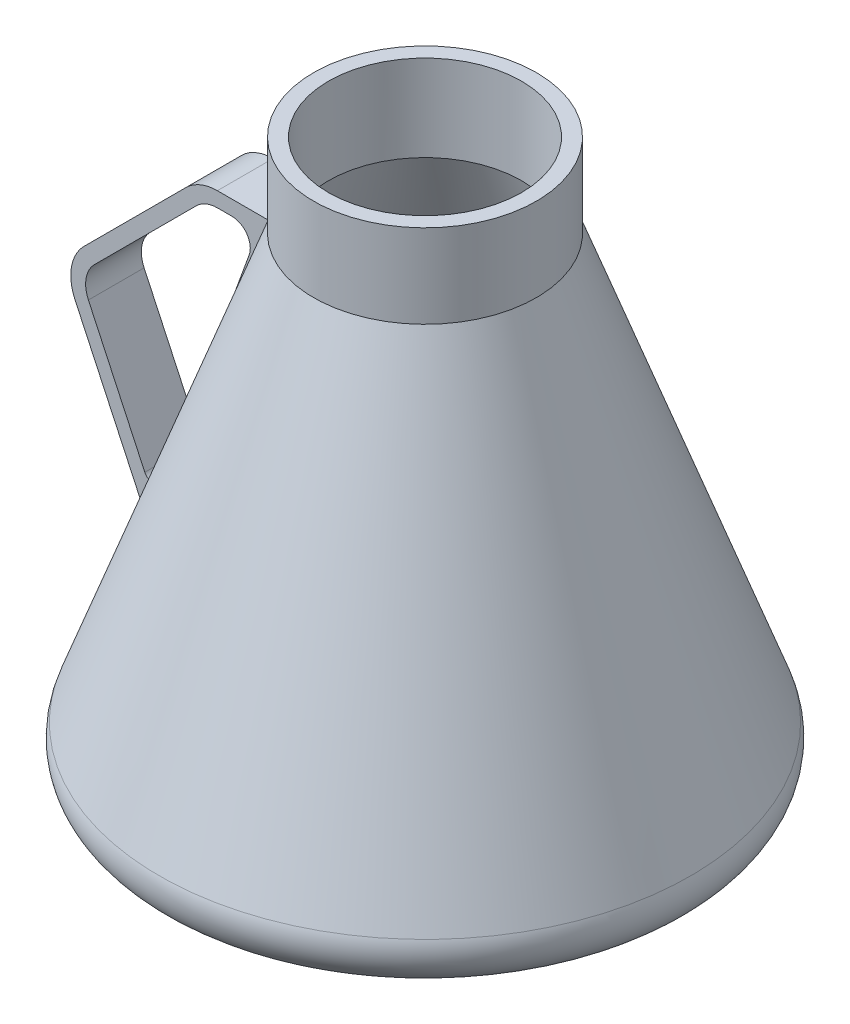
SolidWorks part; units mm, degrees
ref_plane "前视基准面" through (0, 0, 0) normal (0, 0, 1) x (1, 0, 0)
ref_plane "上视基准面" through (0, 0, 0) normal (0, 1, 0) x (1, 0, 0)
ref_plane "右视基准面" through (0, 0, 0) normal (1, 0, 0) x (0, 0, -1)
other "Configuration Table"
sketch "草图1" plane through (0, 0, 0) normal (0, 0, 1) x (1, 0, 0)
  line L0 (0, 0) -> (-124.2494, 0)
  line L1 (-143.0433, 26.8404) -> (-60, 255)
  line L2 (-60, 255) -> (-60, 300)
  line L3 (-60, 300) -> (0, 300)
  line L4 (0, -74.7711) -> (0, 327.4669) construction
  line L5 (0, 0) -> (0, 300)
  line L6 (-8, 8) -> (-124.2494, 8)
  line L7 (-135.5258, 24.1042) -> (-52, 253.5894)
  line L8 (-52, 253.5894) -> (-52, 292)
  line L9 (-52, 292) -> (-8, 292)
  line L10 (-8, 8) -> (-8, 292)
  arc A0 (-143.0433, 26.8404) -> (-124.2494, 0) centre (-124.2494, 20) ccw
  arc A1 (-135.5258, 24.1042) -> (-124.2494, 8) centre (-124.2494, 20) ccw
  dimension "D5" = 20
  dimension "D1" = 300
  dimension "D2" = 20
  dimension "D3" = 60
  dimension "D4" = 45
  dimension "D6" = 8
revolve "旋转2" add sketch "草图1" angle 360 about L4
sketch "草图2" plane through (0, 300, 0) normal (0, 1, 0) x (1, 0, 0)
  circle A0 centre (0, 0) radius 52
  dimension "D1" = 104
extrude "切除-拉伸1" cut sketch "草图2" against normal blind 292
sketch "草图5" plane through (0, 0, 0) normal (0, 0, 1) x (1, 0, 0)
  line L0 (-69.0993, 230) -> (-96.815, 230)
  line L1 (-143.0433, 26.8404) -> (-60, 255) construction
  line L2 (-110.9571, 224.1421) -> (-165.9075, 169.1918)
  line L3 (-169.8915, 146.5973) -> (-130.3326, 61.7628)
  line L4 (-60, 300) -> (0, 300) construction
  line L5 (-69.0993, 230) -> (-130.3326, 61.7628)
  line L6 (-113.7855, 226.9706) -> (-168.7359, 172.0202)
  line L7 (-173.5168, 144.9068) -> (-129.8766, 51.3203)
  line L8 (-63.3867, 234) -> (-129.8766, 51.3203)
  line L9 (-63.3867, 234) -> (-96.815, 234)
  line L10 (-108.1287, 221.3137) -> (-163.0791, 166.3633)
  line L11 (-166.2663, 148.2877) -> (-130.7885, 72.2054)
  line L12 (-74.8118, 226) -> (-130.7885, 72.2054)
  line L13 (-74.8118, 226) -> (-96.815, 226)
  arc A0 (-169.8915, 146.5973) -> (-165.9075, 169.1918) centre (-151.7654, 155.0496) cw
  arc A1 (-96.815, 230) -> (-110.9571, 224.1421) centre (-96.815, 210) ccw
  arc A2 (-173.5168, 144.9068) -> (-168.7359, 172.0202) centre (-151.7654, 155.0496) cw
  arc A3 (-96.815, 234) -> (-113.7855, 226.9706) centre (-96.815, 210) ccw
  arc A4 (-166.2663, 148.2877) -> (-163.0791, 166.3633) centre (-151.7654, 155.0496) cw
  arc A5 (-96.815, 226) -> (-108.1287, 221.3137) centre (-96.815, 210) ccw
  point P10 (-175.8099, 159.2893)
  point P13 (-105.0993, 230)
  dimension "D6" = 20
  dimension "D1" = 100
  dimension "D2" = 110
  dimension "D3" = 36
  dimension "D4" = 70
  dimension "D5" = 135
  dimension "D7" = 4
  dimension "D8" = 4
extrude "凸台-拉伸2" add sketch "草图5" along normal mid plane 30 contours L9 A3 L6 A2 L7 L8 A1 L0 L5 L3 A0 L2 | L0 A1 L2 A0 L3 L5 A5 L13 L12 L11 A4 L10
fillet "圆角1" radius 10 1 edges at (-74.8118, 226, 0)
fillet "圆角2" radius 5 1 edges at (-130.7885, 72.2054, 0)
fillet "圆角3" radius 5 1 edges at (-67.6434, 234, 0)
